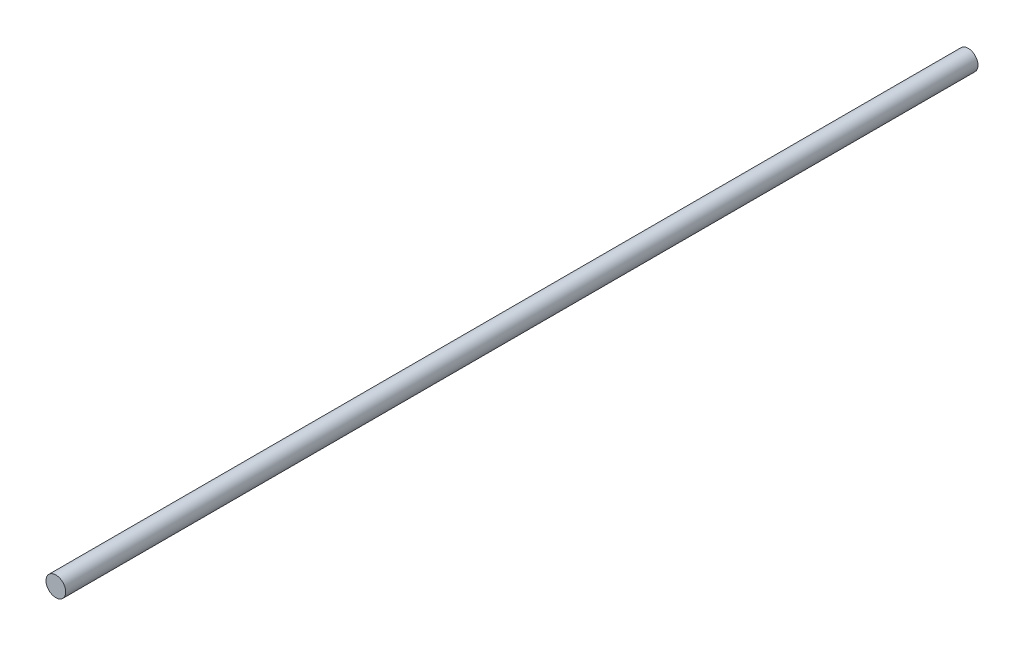
SolidWorks part; units mm, degrees
material "合金钢"
ref_plane "前视基准面" through (0, 0, 0) normal (0, 0, 1) x (1, 0, 0)
ref_plane "上视基准面" through (0, 0, 0) normal (0, 1, 0) x (1, 0, 0)
ref_plane "右视基准面" through (0, 0, 0) normal (1, 0, 0) x (0, 0, -1)
sketch "草图1" plane through (0, 0, 0) normal (0, 0, 1) x (1, 0, 0)
  circle A0 centre (0, 0) radius 4
  dimension "D1" = 8
extrude "凸台-拉伸1" add sketch "草图1" along normal blind 370
